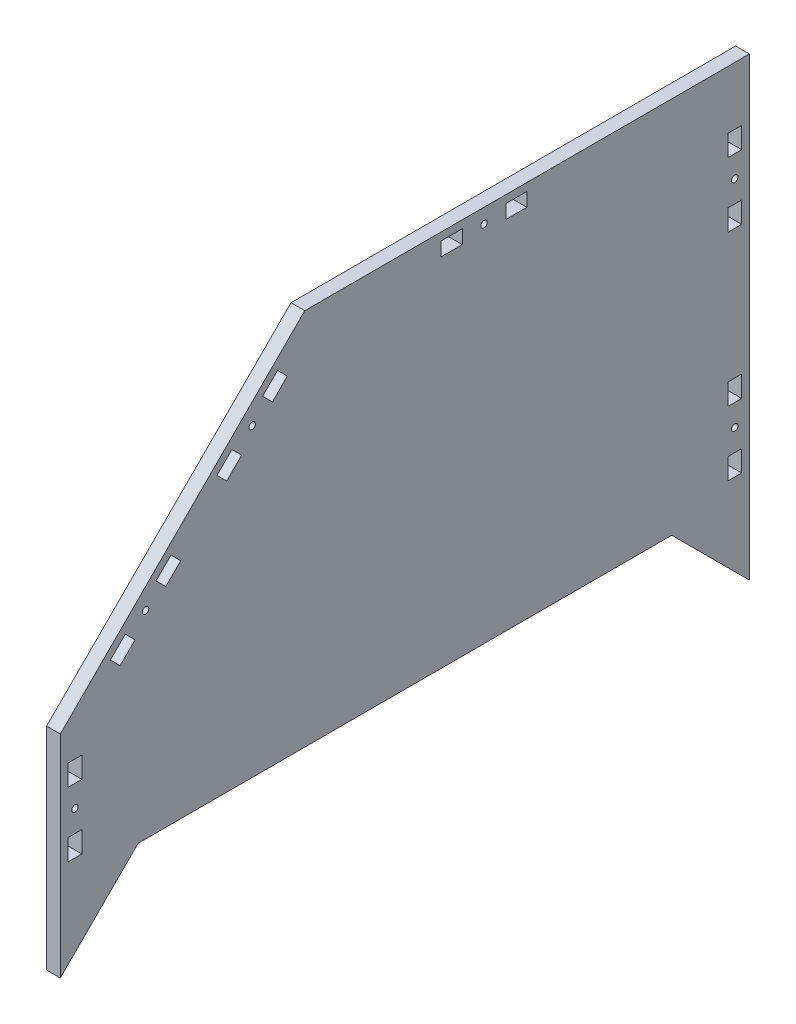
SolidWorks part; units mm, degrees
material "Acrylic (Medium-high impact)"
ref_plane "Front Plane" through (0, 0, 0) normal (0, 0, 1) x (1, 0, 0)
ref_plane "Top Plane" through (0, 0, 0) normal (0, 1, 0) x (1, 0, 0)
ref_plane "Right Plane" through (0, 0, 0) normal (1, 0, 0) x (0, 0, -1)
sketch "Sketch1" plane through (0, 0, 0) normal (1, 0, 0) x (0, 0, -1)
  line L0 (-132.8234, 28.786) -> (114.9766, 28.786)
  line L1 (-168.9234, -7.314) -> (-132.8234, 28.786)
  line L2 (151.0766, -7.314) -> (114.9766, 28.786)
  line L3 (-55.4141, 204.2953) -> (151.0766, 204.2953)
  line L4 (-168.9234, 90.786) -> (-168.9234, -7.314)
  line L5 (151.0766, 204.2953) -> (151.0766, -7.314)
  line L6 (147.475, 137.5806) -> (141.075, 137.5806)
  line L7 (147.475, 177.3806) -> (147.475, 167.5806)
  line L8 (147.475, 67.5806) -> (141.075, 67.5806)
  line L9 (147.475, 77.3806) -> (147.475, 67.5806)
  line L10 (141.075, 77.3806) -> (147.475, 77.3806)
  line L11 (147.475, 37.5806) -> (141.075, 37.5806)
  line L12 (141.075, 37.5806) -> (141.075, 47.3806)
  line L13 (141.075, 47.3806) -> (147.475, 47.3806)
  line L14 (141.075, 77.3806) -> (147.475, 77.3806)
  line L15 (147.475, 77.3806) -> (147.475, 67.5806)
  line L16 (147.475, 67.5806) -> (141.075, 67.5806)
  line L17 (141.075, 67.5806) -> (141.075, 77.3806)
  line L18 (147.475, 37.5806) -> (141.075, 37.5806)
  line L19 (141.075, 37.5806) -> (141.075, 47.3806)
  line L20 (141.075, 47.3806) -> (147.475, 47.3806)
  line L21 (147.475, 47.3806) -> (147.475, 37.5806)
  line L22 (47.7313, 200.6953) -> (47.7313, 194.2953)
  line L23 (7.9313, 200.6953) -> (17.7313, 200.6953)
  line L24 (7.9313, 200.6953) -> (17.7313, 200.6953)
  line L25 (-168.9234, 90.786) -> (-55.4141, 204.2953)
  line L26 (147.475, 177.3806) -> (147.475, 167.5806)
  line L27 (141.075, 147.3806) -> (147.475, 147.3806)
  line L28 (141.075, 167.5806) -> (141.075, 177.3806)
  line L29 (141.075, 137.5806) -> (141.075, 147.3806)
  line L30 (147.475, 167.5806) -> (141.075, 167.5806)
  line L31 (141.075, 137.5806) -> (141.075, 147.3806)
  line L32 (141.075, 177.3806) -> (147.475, 177.3806)
  line L33 (147.475, 137.5806) -> (141.075, 137.5806)
  line L34 (141.075, 147.3806) -> (147.475, 147.3806)
  line L35 (147.475, 147.3806) -> (147.475, 137.5806)
  line L36 (147.475, 167.5806) -> (141.075, 167.5806)
  line L37 (141.075, 177.3806) -> (147.475, 177.3806)
  line L38 (37.9313, 194.2953) -> (37.9313, 200.6953)
  line L39 (17.7313, 194.2953) -> (7.9313, 194.2953)
  line L40 (47.7313, 194.2953) -> (37.9313, 194.2953)
  line L41 (17.7313, 200.6953) -> (17.7313, 194.2953)
  line L42 (47.7313, 194.2953) -> (37.9313, 194.2953)
  line L43 (7.9313, 194.2953) -> (7.9313, 200.6953)
  line L44 (47.7313, 200.6953) -> (47.7313, 194.2953)
  line L45 (37.9313, 194.2953) -> (37.9313, 200.6953)
  line L46 (37.9313, 200.6953) -> (47.7313, 200.6953)
  line L47 (17.7313, 200.6953) -> (17.7313, 194.2953)
  line L48 (7.9313, 194.2953) -> (7.9313, 200.6953)
  line L49 (-68.044, 186.5742) -> (-63.5185, 182.0487)
  line L50 (-96.1869, 158.4313) -> (-89.2572, 165.361)
  line L51 (-96.1869, 158.4313) -> (-89.2572, 165.361)
  line L52 (-70.4482, 175.119) -> (-74.9737, 179.6445)
  line L53 (-84.7317, 160.8355) -> (-91.6614, 153.9058)
  line L54 (-63.5185, 182.0487) -> (-70.4482, 175.119)
  line L55 (-89.2572, 165.361) -> (-84.7317, 160.8355)
  line L57 (-91.6614, 153.9058) -> (-96.1869, 158.4313)
  line L58 (-68.044, 186.5742) -> (-63.5185, 182.0487)
  line L60 (-74.9737, 179.6445) -> (-68.044, 186.5742)
  line L61 (-89.2572, 165.361) -> (-84.7317, 160.8355)
  line L62 (-91.6614, 153.9058) -> (-96.1869, 158.4313)
  line L64 (-113.0161, 132.5511) -> (-117.5416, 137.0766)
  line L65 (-124.4712, 130.147) -> (-119.9457, 125.6215)
  line L66 (-138.7548, 115.8634) -> (-145.6844, 108.9338)
  line L67 (-134.2293, 111.3379) -> (-138.7548, 115.8634)
  line L68 (-145.6844, 108.9338) -> (-141.1589, 104.4083)
  line L69 (-113.0161, 132.5511) -> (-117.5416, 137.0766)
  line L70 (-141.1589, 104.4083) -> (-134.2293, 111.3379)
  line L71 (-124.4712, 130.147) -> (-119.9457, 125.6215)
  line L72 (-141.1589, 104.4083) -> (-134.2293, 111.3379)
  line L73 (-119.9457, 125.6215) -> (-113.0161, 132.5511)
  line L74 (-134.2293, 111.3379) -> (-138.7548, 115.8634)
  line L75 (-117.5416, 137.0766) -> (-124.4712, 130.147)
  line L76 (-117.5416, 137.0766) -> (-124.4712, 130.147)
  line L77 (-145.6844, 108.9338) -> (-141.1589, 104.4083)
  line L78 (-165.3218, 47.3806) -> (-165.3218, 37.5806)
  line L79 (-158.9218, 47.3806) -> (-165.3218, 47.3806)
  line L80 (-158.9218, 37.5806) -> (-158.9218, 47.3806)
  line L81 (-165.3218, 37.5806) -> (-158.9218, 37.5806)
  line L82 (-158.9218, 67.5806) -> (-158.9218, 77.3806)
  line L83 (-165.3218, 67.5806) -> (-158.9218, 67.5806)
  line L84 (-165.3218, 77.3806) -> (-165.3218, 67.5806)
  line L85 (-158.9218, 77.3806) -> (-165.3218, 77.3806)
  line L86 (-158.9218, 47.3806) -> (-165.3218, 47.3806)
  line L87 (-158.9218, 37.5806) -> (-158.9218, 47.3806)
  line L88 (-165.3218, 37.5806) -> (-158.9218, 37.5806)
  line L89 (-158.9218, 77.3806) -> (-165.3218, 77.3806)
  line L90 (-165.3218, 77.3806) -> (-165.3218, 67.5806)
  line L91 (-165.3218, 67.5806) -> (-158.9218, 67.5806)
  line L95 (151.0766, 204.2953) -> (26.5679, 204.2953)
  line L99 (26.5679, 204.2953) -> (7.7277, 204.2953)
  circle A0 centre (144.275, 57.4806) radius 1.5
  circle A1 centre (144.275, 157.4806) radius 1.5
  circle A2 centre (27.8313, 197.4953) radius 1.5
  circle A3 centre (-79.8527, 170.24) radius 1.5
  circle A4 centre (-129.3502, 120.7425) radius 1.5
  circle A5 centre (-162.1218, 57.4806) radius 1.5
extrude "Boss-Extrude1" add sketch "Sketch1" along normal blind 6.4
